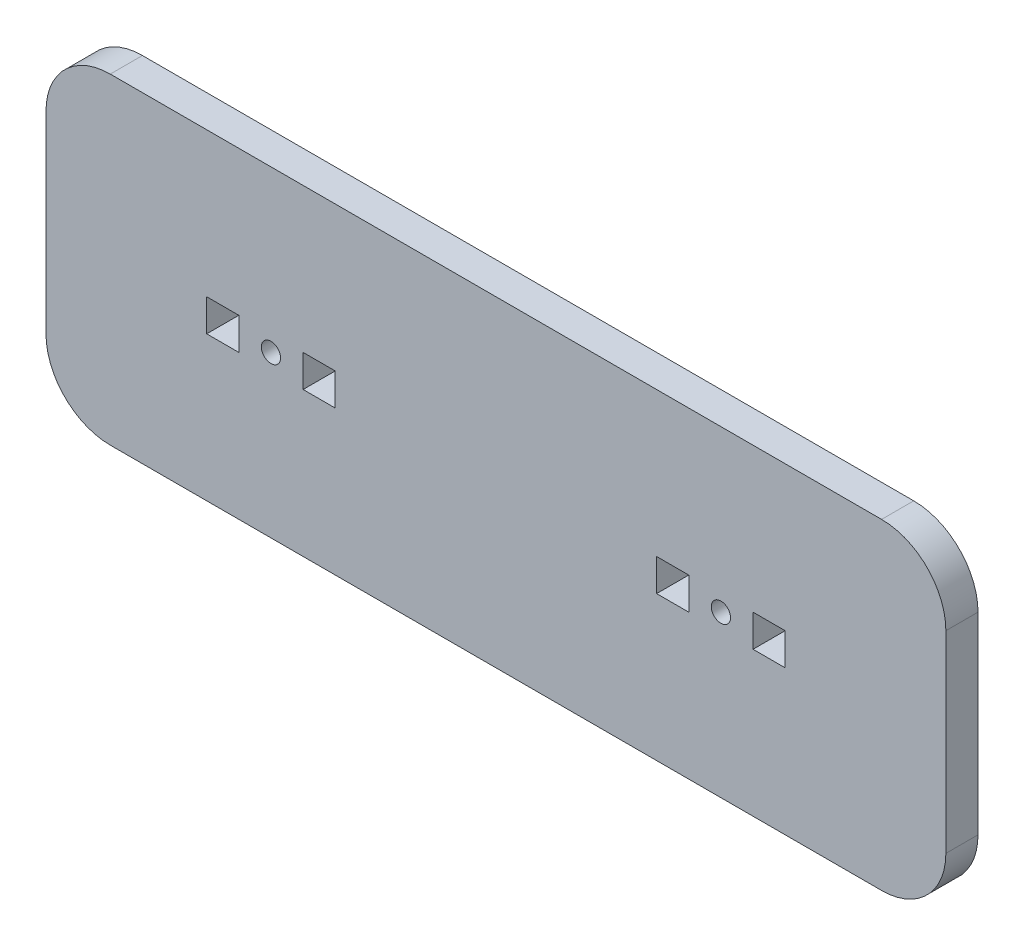
SolidWorks part; units mm, degrees
ref_plane "Front Plane" through (0, 0, 0) normal (0, 0, 1) x (1, 0, 0)
ref_plane "Top Plane" through (0, 0, 0) normal (0, 1, 0) x (1, 0, 0)
ref_plane "Right Plane" through (0, 0, 0) normal (1, 0, 0) x (0, 0, -1)
sketch "Sketch1" plane through (0, 0, 0) normal (0, 0, 1) x (1, 0, 0)
  line L0 (0, 0) -> (221.8095, 0) construction
  line L1 (-70, -25) -> (70, -25)
  line L2 (-70, -25) -> (-70, 25)
  line L3 (-70, 25) -> (70, 25)
  line L4 (70, -25) -> (70, 25)
  line L5 (-70, -25) -> (70, 25) construction
  line L6 (-70, 25) -> (70, -25) construction
  line L7 (0, 0) -> (0, 56.5627) construction
  point P0 (0, 0)
  point P8 (0, 0)
  point P9 (-51.891, 0)
  line B0 (30, 2.5) -> (25, 2.5)
  line B1 (30, 2.5) -> (30, -2.5)
  line B2 (30, -2.5) -> (25, -2.5)
  line B3 (25, 2.5) -> (25, -2.5)
  line B4 (40, 2.5) -> (45, 2.5)
  line B5 (40, 2.5) -> (40, -2.5)
  line B6 (40, -2.5) -> (45, -2.5)
  line B7 (45, 2.5) -> (45, -2.5)
  circle B8 centre (35, 0) radius 1.5
  line B9 (-40, 2.5) -> (-45, 2.5)
  line B10 (-40, 2.5) -> (-40, -2.5)
  line B11 (-40, -2.5) -> (-45, -2.5)
  line B12 (-45, 2.5) -> (-45, -2.5)
  line B13 (-30, 2.5) -> (-25, 2.5)
  line B14 (-30, 2.5) -> (-30, -2.5)
  line B15 (-30, -2.5) -> (-25, -2.5)
  line B16 (-25, 2.5) -> (-25, -2.5)
  circle B17 centre (-35, 0) radius 1.5
  dimension "D1" = 50
  dimension "D2" = 50
  dimension "D3" = 140
sketch_block_instance "Trou M3 plots 5mm-1"
sketch_block "Trou M3 plots 5mm" parameters "D2"=3, "D1"=5, "D3"=5, "D4"=10
sketch_block_instance "Trou M3 plots 5mm-2"
extrude "Boss-Extrude1" add sketch "Sketch1" along normal blind 5
fillet "Fillet1" radius 10 4 edges at (-70, -25, 2.5) (70, -25, 2.5) (70, 25, 2.5) (-70, 25, 2.5)
